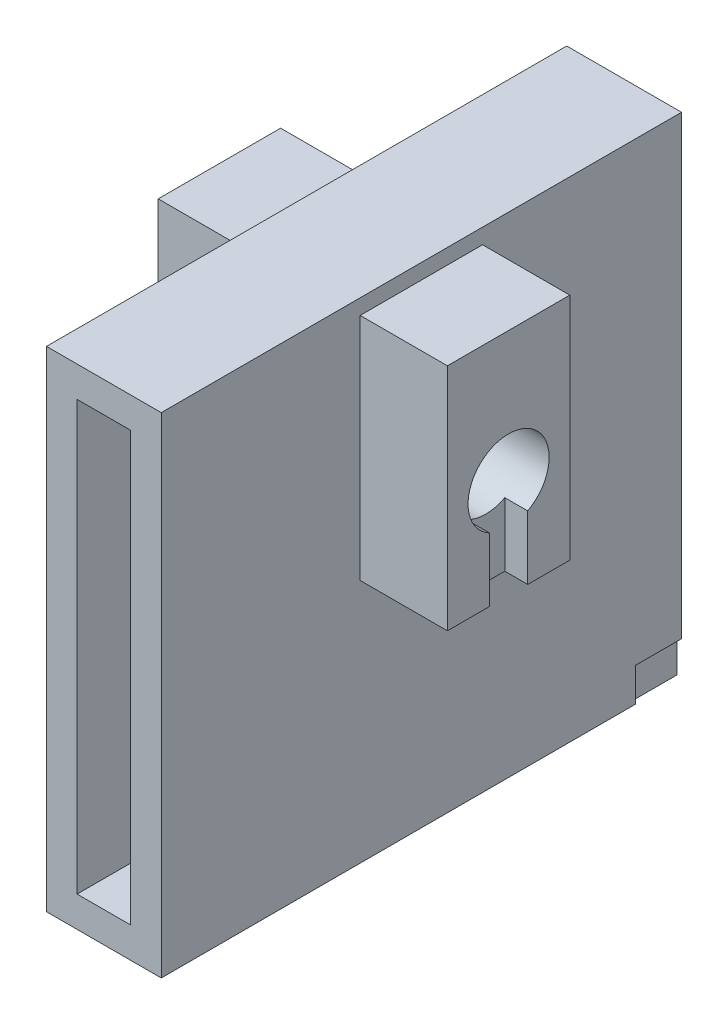
SolidWorks part; units mm, degrees
ref_plane "Спереди" through (0, 0, 0) normal (0, 0, 1) x (1, 0, 0)
ref_plane "Сверху" through (0, 0, 0) normal (0, 1, 0) x (1, 0, 0)
ref_plane "Справа" through (0, 0, 0) normal (1, 0, 0) x (0, 0, -1)
sketch "Эскиз1" plane through (0, 0, 0) normal (1, 0, 0) x (0, 0, -1)
  line L0 (40.8079, 17.2891) -> (6.8079, 17.2891)
  line L1 (40.8079, 17.2891) -> (40.8079, -14.7109)
  line L2 (40.8079, -14.7109) -> (6.8079, -14.7109)
  line L3 (6.8079, 17.2891) -> (6.8079, -14.7109)
  dimension "D1" = 34
  dimension "D2" = 32
extrude "Бобышка-Вытянуть1" add sketch "Эскиз1" along normal blind 7.5
sketch "Эскиз2" plane through (0, 0, -40.8079) normal (0, 0, -1) x (-1, 0, 0)
  line L0 (-7.5, -14.7109) -> (-7.5, 17.2891) construction
  line L1 (-5.5, 15.2891) -> (-2, 15.2891)
  line L2 (-5.5, 15.2891) -> (-5.5, -12.7109)
  line L3 (-5.5, -12.7109) -> (-2, -12.7109)
  line L4 (-2, 15.2891) -> (-2, -12.7109)
  line L5 (0, -14.7109) -> (0, 17.2891) construction
  line L6 (-7.5, -14.7109) -> (0, -14.7109) construction
  line L7 (-7.5, 17.2891) -> (0, 17.2891) construction
  dimension "D1" = 2
  dimension "D2" = 2
  dimension "D3" = 2
  dimension "D4" = 2
  dimension "D5" = 3.5
extrude "Вырез-Вытянуть1" cut sketch "Эскиз2" against normal up to surface (34 mm away) up to face at (3.75, 1.2891, -6.8079)
sketch "Эскиз3" plane through (7.5, 0, 0) normal (1, 0, 0) x (0, 0, -1)
  line L0 (6.8079, -14.7109) -> (40.8079, -14.7109) construction
  line L1 (40.8079, -14.7109) -> (40.8079, 17.2891) construction
  line L2 (6.8079, 17.2891) -> (6.8079, -14.7109) construction
  line L4 (23.8079, 17.2891) -> (23.8079, -14.4826) construction
  line L5 (40.8079, 17.2891) -> (6.8079, 17.2891) construction
  line L6 (6.8079, 1.2891) -> (40.8079, 1.2891) construction
  line L7 (21.6079, 3.2891) -> (26.0079, 3.2891)
  line L8 (21.6079, 14.2891) -> (26.0079, 14.2891)
  line L9 (21.6079, 14.2891) -> (21.6079, 3.2891)
  line L10 (26.0079, 14.2891) -> (26.0079, 3.2891)
  point P18 (23.8079, 7.7891)
  dimension "D1" = 29
  dimension "D2" = 18
  dimension "D4" = 4.4
  dimension "D5" = 2.2
extrude "Вырез-Вытянуть2" cut sketch "Эскиз3" against normal through all
sketch "Эскиз5" plane through (7.5, 0, 0) normal (1, 0, 0) x (0, 0, -1)
  line L0 (6.8079, 1.2891) -> (40.8079, 1.2891) construction
  line L1 (6.8079, 17.2891) -> (6.8079, -14.7109) construction
  line L2 (19.8079, 1.2891) -> (27.8079, 1.2891)
  line L3 (19.8079, 16.2891) -> (27.8079, 16.2891)
  line L4 (19.8079, 16.2891) -> (19.8079, 1.2891)
  line L5 (27.8079, 16.2891) -> (27.8079, 1.2891)
  line L6 (40.8079, -14.7109) -> (40.8079, 17.2891) construction
  line L7 (23.8079, 17.2891) -> (23.8079, -14.7109) construction
  line L8 (40.8079, 17.2891) -> (6.8079, 17.2891) construction
  line L9 (6.8079, -14.7109) -> (40.8079, -14.7109) construction
  dimension "D1" = 8
  dimension "D2" = 16
  dimension "D3" = 31
  dimension "D4" = 4
  dimension "D5" = 17
extrude "Бобышка-Вытянуть2" add sketch "Эскиз5" along normal blind 5.7 separate body
sketch "Эскиз7" plane through (0, 0, 0) normal (-1, 0, 0) x (0, 0, 1)
  line L0 (-23.8079, 17.2891) -> (-23.8079, -14.7109) construction
  line L1 (-27.8079, 1.2891) -> (-19.8079, 1.2891)
  line L2 (-27.8079, 16.2891) -> (-19.8079, 16.2891)
  line L3 (-27.8079, 16.2891) -> (-27.8079, 1.2891)
  line L4 (-19.8079, 16.2891) -> (-19.8079, 1.2891)
  line L5 (-40.8079, 17.2891) -> (-6.8079, 17.2891) construction
  line L6 (-6.8079, -14.7109) -> (-40.8079, -14.7109) construction
  line L7 (-40.8079, 1.2891) -> (-6.8079, 1.2891) construction
  line L8 (-40.8079, -14.7109) -> (-40.8079, 17.2891) construction
  line L9 (-6.8079, 17.2891) -> (-6.8079, -14.7109) construction
  dimension "D1" = 8
  dimension "D2" = 16
  dimension "D3" = 31
  dimension "D4" = 4
extrude "Бобышка-Вытянуть3" add sketch "Эскиз7" along normal blind 5.7 separate body
sketch "Эскиз9" plane through (13.2, 0, 0) normal (1, 0, 0) x (0, 0, -1)
  line L0 (6.8079, -14.7109) -> (40.8079, -14.7109) construction
  line L1 (6.8079, 17.2891) -> (6.8079, -14.7109) construction
  circle A0 centre (23.8079, 7.7891) radius 2.65
  dimension "D3" = 5.3
  dimension "D1" = 22.5
  dimension "D2" = 17
extrude "Вырез-Вытянуть5" cut sketch "Эскиз9" against normal through all
sketch "Эскиз13" plane through (-5.7, 0, 0) normal (-1, 0, 0) x (0, 0, 1)
  line L0 (-23.8079, 16.2891) -> (-23.8079, 1.2891) construction
  line L1 (-19.8079, 16.2891) -> (-27.8079, 16.2891) construction
  line L2 (-27.8079, 1.2891) -> (-19.8079, 1.2891) construction
  line L4 (-25.2079, 5.5511) -> (-22.4079, 5.5511)
  line L5 (-25.2079, 5.5511) -> (-25.2079, 1.2354)
  line L6 (-25.2079, 1.2354) -> (-22.4079, 1.2354)
  line L7 (-22.4079, 5.5511) -> (-22.4079, 1.2354)
  line L8 (-25.2079, 5.5511) -> (-22.4079, 1.2354) construction
  line L9 (-25.2079, 1.2354) -> (-22.4079, 5.5511) construction
  point P6 (-23.8079, 3.3932)
  dimension "D1" = 2.8
extrude "Вырез-Вытянуть6" cut sketch "Эскиз13" against normal blind 1.5
sketch "Эскиз14" plane through (13.2, 0, 0) normal (1, 0, 0) x (0, 0, -1)
  line L0 (23.8079, 16.2891) -> (23.8079, 1.2891) construction
  line L1 (27.8079, 16.2891) -> (19.8079, 16.2891) construction
  line L2 (19.8079, 1.2891) -> (27.8079, 1.2891) construction
  line L4 (22.5579, 5.5326) -> (25.0579, 5.5326)
  line L5 (22.5579, 5.5326) -> (22.5579, 1.1547)
  line L6 (22.5579, 1.1547) -> (25.0579, 1.1547)
  line L7 (25.0579, 5.5326) -> (25.0579, 1.1547)
  line L8 (22.5579, 5.5326) -> (25.0579, 1.1547) construction
  line L9 (22.5579, 1.1547) -> (25.0579, 5.5326) construction
  point P6 (23.8079, 3.3436)
  dimension "D1" = 2.5
extrude "Вырез-Вытянуть7" cut sketch "Эскиз14" against normal blind 1.5
sketch "Эскиз15" plane through (0, 0, -40.8079) normal (0, 0, -1) x (-1, 0, 0)
  line L0 (-7.5, -14.7109) -> (-7.5, 17.2891) construction
  line L1 (-5.5, -12.7109) -> (-7.5, -12.7109)
  line L2 (-5.5, -12.7109) -> (-5.5, -12.5096)
  line L3 (-5.5, -12.5096) -> (-7.5, -12.5096)
  line L4 (-7.5, -12.7109) -> (-7.5, -12.5096)
  line L5 (0, -14.7109) -> (0, 17.2891) construction
  line L6 (-2, -12.7109) -> (0, -12.7109)
  line L7 (-2, -12.7109) -> (-2, -12.5096)
  line L8 (-2, -12.5096) -> (0, -12.5096)
  line L9 (0, -12.7109) -> (0, -12.5096)
extrude "Вырез-Вытянуть8" cut sketch "Эскиз15" against normal blind 3
sketch "Эскиз16" plane through (0, 0, 0) normal (-1, 0, 0) x (0, 0, 1)
  line L0 (-6.8079, -14.7109) -> (-40.8079, -14.7109) construction
  line L1 (-40.8079, -12.7109) -> (-37.8043, -12.7109)
  line L2 (-40.8079, -12.7109) -> (-40.8079, -14.7109)
  line L3 (-40.8079, -14.7109) -> (-37.8043, -14.7109)
  line L4 (-37.8043, -12.7109) -> (-37.8043, -14.7109)
extrude "Вырез-Вытянуть9" cut sketch "Эскиз16" against normal blind 0.3
sketch "Эскиз17" plane through (7.5, 0, 0) normal (1, 0, 0) x (0, 0, -1)
  line L1 (40.8079, -14.7109) -> (37.8079, -14.7109)
  line L2 (40.8079, -14.7109) -> (40.8079, -12.7109)
  line L3 (40.8079, -12.7109) -> (37.8079, -12.7109)
  line L4 (37.8079, -14.7109) -> (37.8079, -12.7109)
extrude "Вырез-Вытянуть10" cut sketch "Эскиз17" against normal blind 0.3
equation "\"D2@Эскиз2\"=\"D1@Эскиз2\""
equation "\"D3@Эскиз2\"=\"D1@Эскиз2\""
equation "\"D4@Эскиз2\"=\"D3@Эскиз2\""
